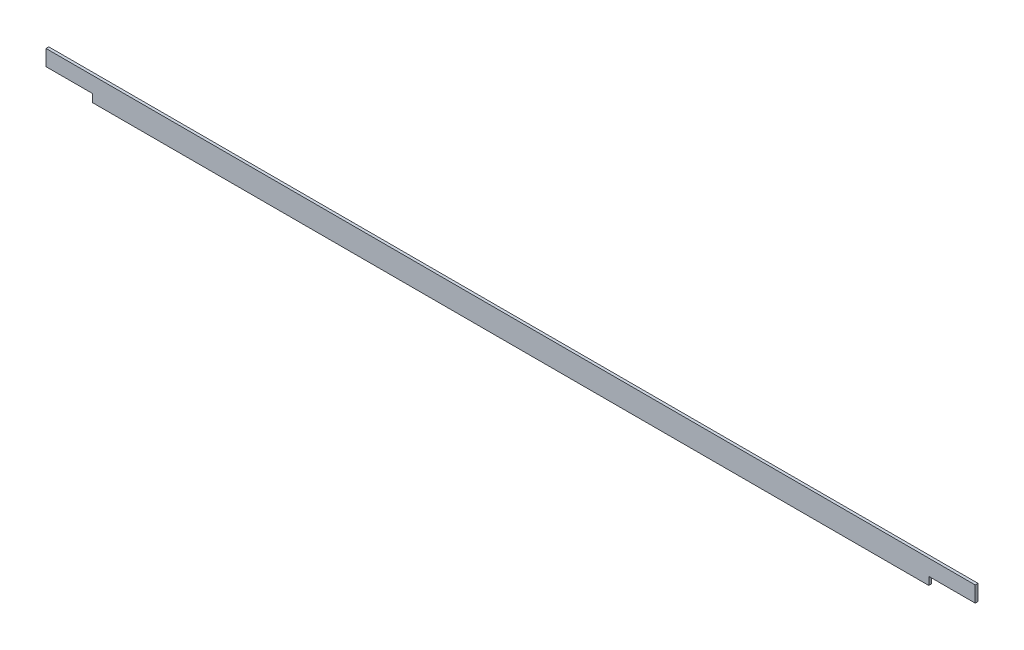
SolidWorks part; units mm, degrees
ref_plane "Front Plane" through (0, 0, 0) normal (0, 0, 1) x (1, 0, 0)
ref_plane "Top Plane" through (0, 0, 0) normal (0, 1, 0) x (1, 0, 0)
ref_plane "Right Plane" through (0, 0, 0) normal (1, 0, 0) x (0, 0, -1)
sketch "Sketch2" plane through (0, 0, 0) normal (0, 0, 1) x (1, 0, 0)
  line L1 (-500, -8.5) -> (500, -8.5)
  line L2 (-500, -8.5) -> (-500, 8.5)
  line L3 (-500, 8.5) -> (500, 8.5)
  line L4 (500, -8.5) -> (500, 8.5)
  line L5 (-500, -8.5) -> (500, 8.5) construction
  line L6 (-500, 8.5) -> (500, -8.5) construction
  line L7 (-450, -8.5) -> (450, -8.5)
  line L8 (-450, -8.5) -> (-450, -17)
  line L9 (-450, -17) -> (450, -17)
  line L10 (450, -8.5) -> (450, -17)
  point P0 (0, 0)
  dimension "D1" = 17
  dimension "D2" = 1000
  dimension "D3" = 8.5
  dimension "D4" = 50
  dimension "D5" = 900
extrude "Boss-Extrude1" add sketch "Sketch2" along normal mid plane 3 contours L10 L1 L8 L9 | L1 L4 L3 L2
